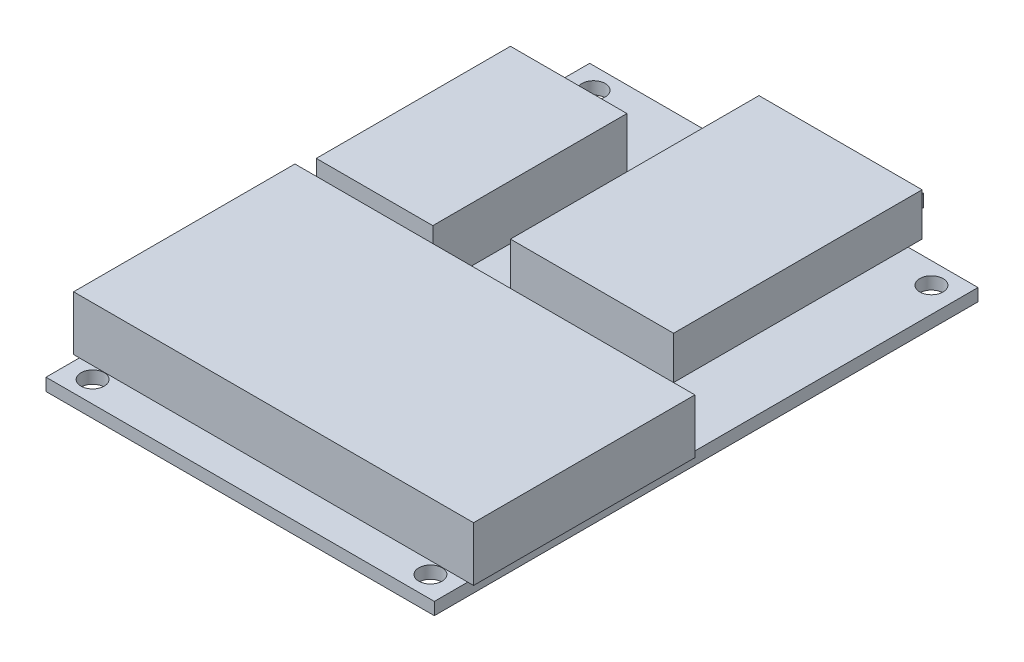
SolidWorks part; units mm, degrees
ref_plane "前视基准面" through (0, 0, 0) normal (0, 0, 1) x (1, 0, 0)
ref_plane "上视基准面" through (0, 0, 0) normal (0, 1, 0) x (1, 0, 0)
ref_plane "右视基准面" through (0, 0, 0) normal (1, 0, 0) x (0, 0, -1)
other "Configuration Table"
sketch "草图1" plane through (0, 0, 0) normal (0, 1, 0) x (1, 0, 0)
  line L0 (25, 0) -> (25, 70) construction
  line L1 (0, 0) -> (50, 0)
  line L2 (0, 0) -> (0, 70)
  line L3 (0, 70) -> (50, 70)
  line L4 (50, 0) -> (50, 70)
  line L5 (0, 35) -> (50, 35) construction
  circle A0 centre (3.25, 2.75) radius 1.5
  circle A1 centre (46.75, 2.75) radius 1.5
  circle A2 centre (46.75, 67.25) radius 1.5
  circle A3 centre (3.25, 67.25) radius 1.5
  dimension "D5" = 3
  dimension "D1" = 50
  dimension "D2" = 70
  dimension "D3" = 43.5
  dimension "D4" = 64.5
extrude "凸台-拉伸1" add sketch "草图1" along normal blind 1.6 contours L2 L3 L4 L1
sketch "草图3" plane through (0, 1.6, 0) normal (0, 1, 0) x (1, 0, 0)
  line L0 (25, 0) -> (25, 35) construction
  line L1 (25, 0) -> (25, 70) construction
  line L2 (0, 0) -> (50, 0) construction
  line L3 (-0.75, 4.3) -> (50.75, 4.3)
  line L4 (-0.75, 4.3) -> (-0.75, 32.8)
  line L5 (-0.75, 32.8) -> (50.75, 32.8)
  line L6 (50.75, 4.3) -> (50.75, 32.8)
  dimension "D1" = 51.5
  dimension "D2" = 4.3
  dimension "D3" = 28.5
extrude "凸台-拉伸2" add sketch "草图3" along normal blind 7
sketch "草图4" plane through (0, 1.6, 0) normal (0, 1, 0) x (1, 0, 0)
  line L0 (0, 0) -> (0, 70) construction
  line L1 (0, 34.8) -> (15, 34.8)
  line L2 (0, 34.8) -> (0, 59.8)
  line L3 (0, 59.8) -> (15, 59.8)
  line L4 (15, 34.8) -> (15, 59.8)
  line L5 (50.75, 32.8) -> (-0.75, 32.8) construction
  dimension "D1" = 2
  dimension "D2" = 15
  dimension "D3" = 25
extrude "凸台-拉伸3" add sketch "草图4" along normal up to surface (7 mm away) up to face at (25, 8.6, -18.55)
sketch "草图5" plane through (0, 1.6, 0) normal (0, 1, 0) x (1, 0, 0)
  line L0 (15, 59.8) -> (15, 34.8) construction
  line L1 (20, 39.8) -> (41, 39.8)
  line L2 (20, 39.8) -> (20, 71.8)
  line L3 (20, 71.8) -> (41, 71.8)
  line L4 (41, 39.8) -> (41, 71.8)
  line L5 (50, 32.8) -> (0, 32.8) construction
  dimension "D1" = 5
  dimension "D2" = 7
  dimension "D3" = 32
  dimension "D4" = 21
extrude "凸台-拉伸4" add sketch "草图5" along normal blind 5.5
sketch "草图6" plane through (0, 0, -70) normal (0, 0, -1) x (-1, 0, 0)
  line L0 (-30.5, 1.6) -> (-30.5, 0) construction
  line L1 (-41, 1.6) -> (-20, 1.6) construction
  line L2 (0, 0) -> (-50, 0) construction
  line L4 (-36, 1.6) -> (-25, 1.6)
  line L5 (-36, 1.6) -> (-36, 0)
  line L6 (-36, 0) -> (-25, 0)
  line L7 (-25, 1.6) -> (-25, 0)
  dimension "D1" = 11
extrude "凸台-拉伸5" add sketch "草图6" along normal blind 7
